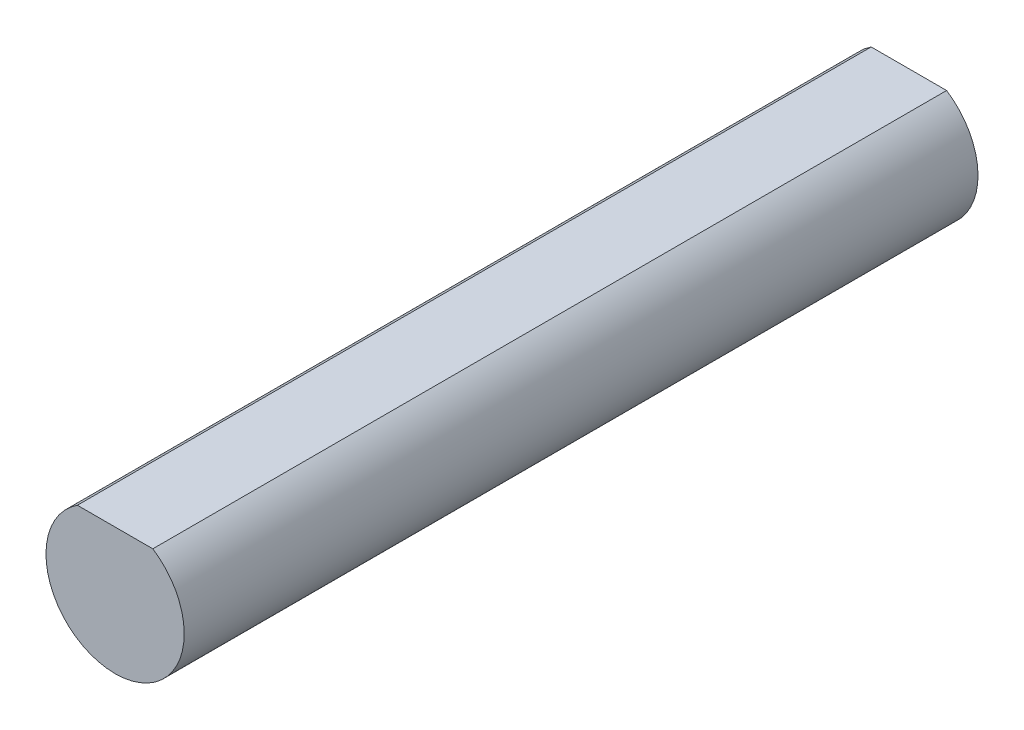
SolidWorks part; units mm, degrees
ref_plane "前视基准面" through (0, 0, 0) normal (0, 0, 1) x (1, 0, 0)
ref_plane "上视基准面" through (0, 0, 0) normal (0, 1, 0) x (1, 0, 0)
ref_plane "右视基准面" through (0, 0, 0) normal (1, 0, 0) x (0, 0, -1)
sketch "草图1" plane through (0, 0, 0) normal (0, 0, 1) x (1, 0, 0)
  circle A0 centre (0, 0) radius 7.4
  dimension "D1" = 14.8
extrude "凸台-拉伸1" add sketch "草图1" along normal blind 85
sketch "草图2" plane through (0, 0, 85) normal (0, 0, 1) x (1, 0, 0)
  line L1 (-11.4614, 11.0949) -> (11.5002, 11.0949)
  line L2 (-11.4614, 11.0949) -> (-11.4614, 6.2)
  line L3 (-11.4614, 6.2) -> (11.5002, 6.2)
  line L4 (11.5002, 11.0949) -> (11.5002, 6.2)
  dimension "D1" = 6.2
extrude "切除-拉伸1" cut sketch "草图2" against normal through all
